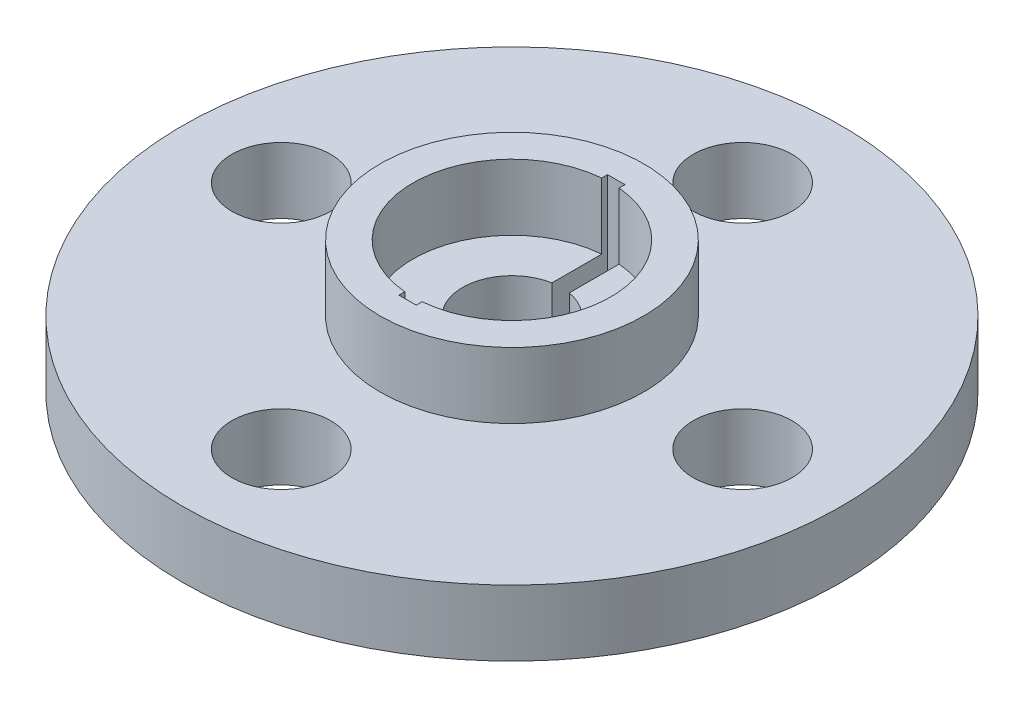
SolidWorks part; units mm, degrees
ref_plane "前视基准面" through (0, 0, 0) normal (0, 0, 1) x (1, 0, 0)
ref_plane "上视基准面" through (0, 0, 0) normal (0, 1, 0) x (1, 0, 0)
ref_plane "右视基准面" through (0, 0, 0) normal (1, 0, 0) x (0, 0, -1)
other "Configuration Table"
sketch "草图1" plane through (0, 0, 0) normal (0, 1, 0) x (1, 0, 0)
  circle A0 centre (0, 0) radius 10
  circle A1 centre (0, 0) radius 7 construction
  circle A2 centre (7, 0) radius 1.5
  circle A3 centre (0, 0) radius 1.5
  circle A4 centre (0, -7) radius 1.5
  circle A5 centre (-7, 0) radius 1.5
  circle A6 centre (0, 7) radius 1.5
  point P16 (0, 0)
  dimension "D1" = 20
  dimension "D2" = 14
  dimension "D3" = 3
  dimension "D4" = 3
  dimension "D5" = 4
extrude "凸台-拉伸1" add sketch "草图1" along normal blind 2
sketch "草图2" plane through (0, 2, 0) normal (0, 1, 0) x (1, 0, 0)
  circle A0 centre (0, 0) radius 4
  circle A1 centre (0, 0) radius 3
  dimension "D1" = 8
  dimension "D2" = 6
extrude "凸台-拉伸2" add sketch "草图2" along normal blind 2
sketch "草图3" plane through (0, 0, 0) normal (0, -1, 0) x (1, 0, 0)
  line L1 (-0.2632, -3.1665) -> (0.2632, -3.1665)
  line L2 (-0.2632, -3.1665) -> (-0.2632, 3.1665)
  line L3 (-0.2632, 3.1665) -> (0.2632, 3.1665)
  line L4 (0.2632, -3.1665) -> (0.2632, 3.1665)
  line L5 (-0.2632, -3.1665) -> (0.2632, 3.1665) construction
  line L6 (-0.2632, 3.1665) -> (0.2632, -3.1665) construction
  point P0 (0, 0)
extrude "切除-拉伸1" cut sketch "草图3" against normal blind 4
